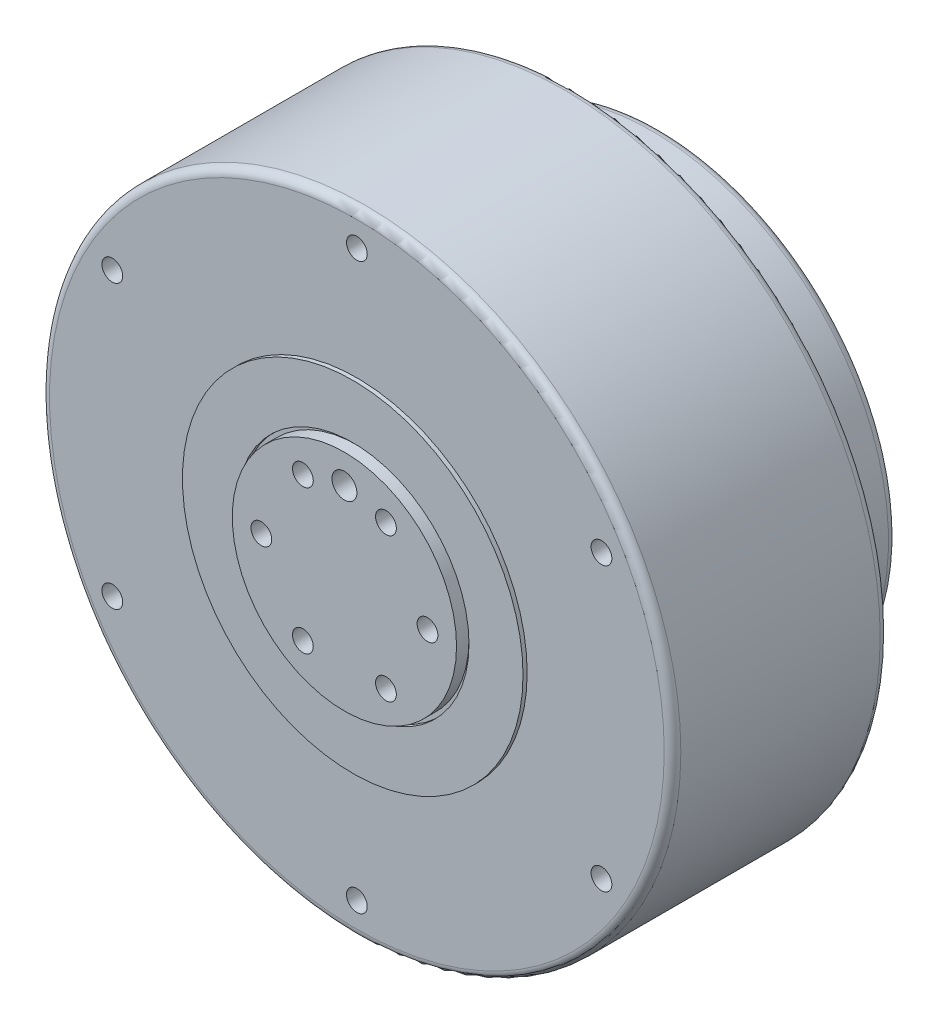
SolidWorks part; units mm, degrees
ref_plane "Ön Düzlem" through (0, 0, 0) normal (0, 0, 1) x (1, 0, 0)
ref_plane "Üst Düzlem" through (0, 0, 0) normal (0, 1, 0) x (1, 0, 0)
ref_plane "Sağ Düzlem" through (0, 0, 0) normal (1, 0, 0) x (0, 0, -1)
sketch "Çizim2" plane through (0, 0, 0) normal (0, 0, 1) x (1, 0, 0)
  circle A0 centre (0, 0) radius 38
  dimension "D1" = 76
extrude "Yükseklik-Ekstrüzyon1" add sketch "Çizim2" along normal mid plane 26
sketch "Çizim3" plane through (0, 0, -13) normal (0, 0, -1) x (-1, 0, 0)
  line L0 (-10.4881, -26.5) -> (10.4881, -26.5)
  arc A0 (10.4881, -26.5) -> (-10.4881, -26.5) centre (0, 0) ccw
  dimension "D1" = 57
  dimension "D2" = 55
extrude "Yükseklik-Ekstrüzyon2" add sketch "Çizim3" along normal blind 10.5
sketch "Çizim4" plane through (0, 0, 13) normal (0, 0, 1) x (1, 0, 0)
  circle A0 centre (0, 0) radius 20.5
  circle A1 centre (0, 0) radius 14
  dimension "D1" = 41
  dimension "D2" = 28
extrude "Yükseklik-Ekstrüzyon3" add sketch "Çizim4" along normal blind 0.5
sketch "Çizim5" plane through (0, 0, 13) normal (0, 0, 1) x (1, 0, 0)
  circle A0 centre (0, 0) radius 13.5
  dimension "D1" = 27
extrude "Yükseklik-Ekstrüzyon4" add sketch "Çizim5" along normal blind 1.5
sketch "Çizim7" plane through (0, 0, 13) normal (0, 0, 1) x (1, 0, 0)
  circle A0 centre (0, 0) radius 34 construction
  point P3 (0, 34)
  point P4 (29.4449, 17)
  point P7 (29.4449, -17)
  point P8 (0, -34)
  point P9 (-29.4449, -17)
  point P10 (-29.4449, 17)
  point P11 (0, 0)
  dimension "D1" = 68
  dimension "D2" = 6
sketch "Çizim9" plane through (0, 0, -13) normal (0, 0, -1) x (-1, 0, 0)
  point P0 (29.4449, 17)
  point P2 (29.4449, -17)
  point P4 (0, -34)
  point P6 (-29.4449, -17)
  point P8 (-29.4449, 17)
  point P10 (0, 34)
hole_wizard "Ø2.5 (2.5) Çap Delik1" positions "3B Çizim1" profile "Çizim8" hole size "Ø2.5" standard "ISO"
sketch3d "3B Çizim1"
  point P0 (0, 34, 13)
  point P3 (29.4449, 17, 13)
  point P6 (-29.4449, 17, 13)
  point P9 (-29.4449, -17, 13)
  point P12 (0, -34, 13)
  point P15 (29.4449, -17, 13)
sketch "Çizim8" plane through (0, 34, 13) normal (1, 0, 0) x (0, -1, 0)
  line L0 (0, 0) -> (0, 3.7511)
  line L1 (0, 3.7511) -> (1.25, 3)
  line L2 (1.25, 3) -> (1.25, 0)
  line L5 (1.25, 0) -> (0, 0)
  line L10 (0, 3.7511) -> (-1.25, 3) construction
  line L11 (0, -6.35) -> (0, 107.95) construction
  dimension "Hole Dia." = 2.5
  dimension "Hole Depth" = 3
  dimension "Drill Angle" = 118
cosmetic thread "Kozmetik Diş Açma1" parameters "D2"=3
cosmetic thread "Kozmetik Diş Açma2" parameters "D2"=3
cosmetic thread "Kozmetik Diş Açma3" parameters "D2"=3
cosmetic thread "Kozmetik Diş Açma4" parameters "D2"=3
cosmetic thread "Kozmetik Diş Açma5" parameters "D2"=3
cosmetic thread "Kozmetik Diş Açma6" parameters "D2"=3
hole_wizard "Ø2.5 (2.5) Çap Delik2" positions "3B Çizim2" profile "Çizim10" hole size "Ø2.5" standard "ISO"
sketch3d "3B Çizim2"
  point P0 (0, 34, -13)
  point P3 (29.4449, 17, -13)
  point P6 (29.4449, -17, -13)
  point P9 (0, -34, -13)
  point P12 (-29.4449, -17, -13)
  point P15 (-29.4449, 17, -13)
sketch "Çizim10" plane through (0, 34, -13) normal (1, 0, 0) x (0, 1, 0)
  line L0 (0, 0) -> (0, 3.7511)
  line L1 (0, 3.7511) -> (1.25, 3)
  line L2 (1.25, 3) -> (1.25, 0)
  line L5 (1.25, 0) -> (0, 0)
  line L10 (0, 3.7511) -> (-1.25, 3) construction
  line L11 (0, -6.35) -> (0, 107.95) construction
  dimension "Hole Dia." = 2.5
  dimension "Hole Depth" = 3
  dimension "Drill Angle" = 118
cosmetic thread "Kozmetik Diş Açma7" parameters "D2"=3
cosmetic thread "Kozmetik Diş Açma8" parameters "D2"=3
cosmetic thread "Kozmetik Diş Açma9" parameters "D2"=3
cosmetic thread "Kozmetik Diş Açma10" parameters "D2"=3
cosmetic thread "Kozmetik Diş Açma11" parameters "D2"=3
cosmetic thread "Kozmetik Diş Açma12" parameters "D2"=3
sketch "Çizim11" plane through (0, 0, 14.5) normal (0, 0, 1) x (1, 0, 0)
  circle A0 centre (0, 0) radius 10 construction
  point P3 (10, 0)
  point P4 (0, 10)
  point P5 (5, -8.6603)
  point P8 (-5, -8.6603)
  point P9 (-10, 0)
  point P10 (-5, 8.6603)
  point P11 (5, 8.6603)
  point P12 (0, 0)
  dimension "D1" = 20
  dimension "D2" = 6
hole_wizard "Ø2.5 (2.5) Çap Delik3" positions "3B Çizim3" profile "Çizim12" hole size "Ø2.5" standard "ISO"
sketch3d "3B Çizim3"
  point P0 (-10, 0, 14.5)
  point P3 (-5, 8.6603, 14.5)
  point P6 (5, 8.6603, 14.5)
  point P9 (10, 0, 14.5)
  point P12 (5, -8.6603, 14.5)
  point P15 (-5, -8.6603, 14.5)
sketch "Çizim12" plane through (-10, 0, 14.5) normal (1, 0, 0) x (0, -1, 0)
  line L0 (0, 0) -> (0, 5.7511)
  line L1 (0, 5.7511) -> (1.25, 5)
  line L2 (1.25, 5) -> (1.25, 0)
  line L5 (1.25, 0) -> (0, 0)
  line L10 (0, 5.7511) -> (-1.25, 5) construction
  line L11 (0, -6.35) -> (0, 107.95) construction
  dimension "Hole Dia." = 2.5
  dimension "Hole Depth" = 5
  dimension "Drill Angle" = 118
cosmetic thread "Kozmetik Diş Açma13" parameters "D2"=3
cosmetic thread "Kozmetik Diş Açma14" parameters "D2"=3
cosmetic thread "Kozmetik Diş Açma15" parameters "D2"=3
cosmetic thread "Kozmetik Diş Açma16" parameters "D2"=3
cosmetic thread "Kozmetik Diş Açma17" parameters "D2"=3
cosmetic thread "Kozmetik Diş Açma18" parameters "D2"=3
hole_wizard "Ø3.0 (3) Çap Delik1" positions "3B Çizim4" profile "Çizim13" hole size "Ø3.0" standard "ISO"
sketch3d "3B Çizim4"
  point P0 (0, 10, 14.5)
sketch "Çizim13" plane through (0, 10, 14.5) normal (1, 0, 0) x (0, -1, 0)
  line L0 (0, 0) -> (0, 3.9013)
  line L1 (0, 3.9013) -> (1.5, 3)
  line L2 (1.5, 3) -> (1.5, 0)
  line L5 (1.5, 0) -> (0, 0)
  line L10 (0, 3.9013) -> (-1.5, 3) construction
  line L11 (0, -6.35) -> (0, 107.95) construction
  dimension "Hole Dia." = 3
  dimension "Hole Depth" = 3
  dimension "Drill Angle" = 118
fillet "Radyus1" radius 1 4 edges at (0, -26.5, -23.5) (0, 28.5, -23.5) (38, 0, 13) (38, 0, -13)
